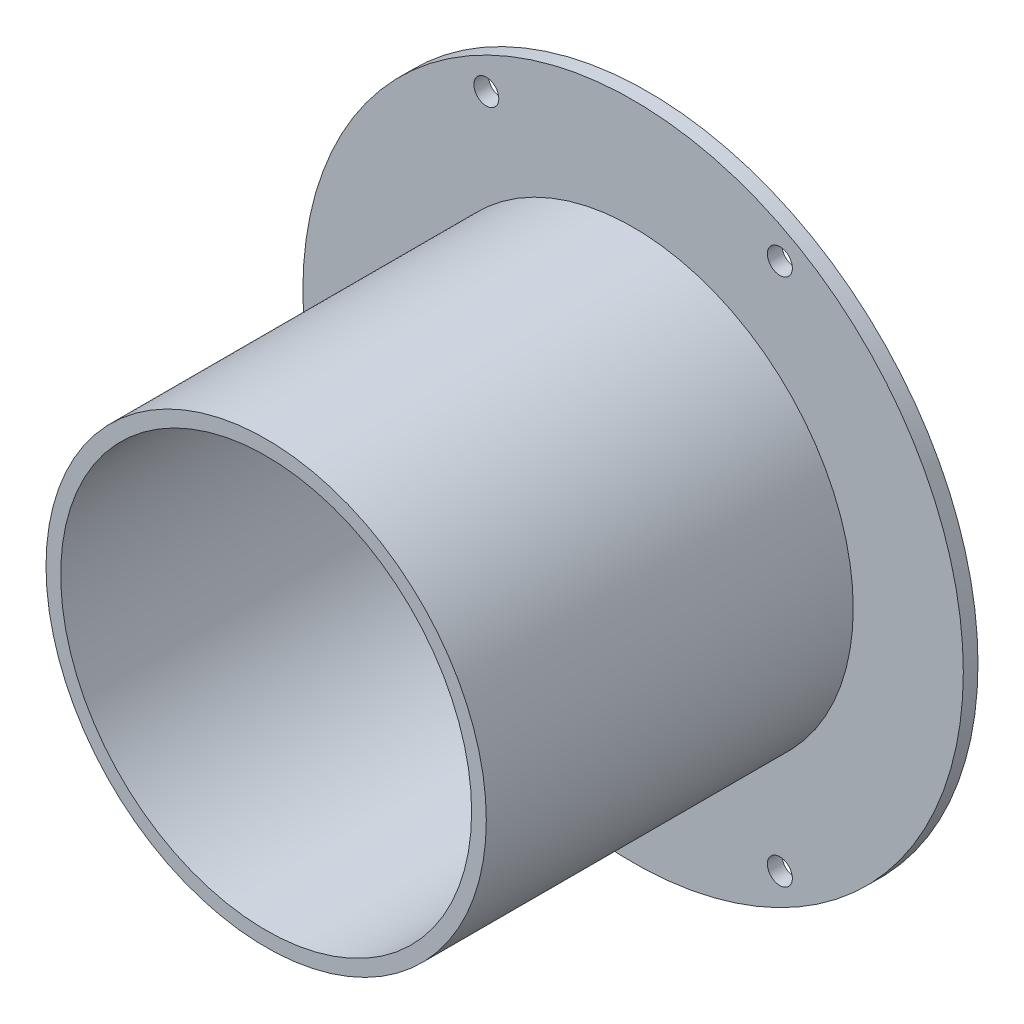
SolidWorks part; units mm, degrees
material "AISI 4340 Steel, normalized"
ref_plane "Front Plane" through (0, 0, 0) normal (0, 0, 1) x (1, 0, 0)
ref_plane "Top Plane" through (0, 0, 0) normal (0, 1, 0) x (1, 0, 0)
ref_plane "Right Plane" through (0, 0, 0) normal (1, 0, 0) x (0, 0, -1)
sketch "Sketch1" plane through (0, 0, 0) normal (0, 0, 1) x (1, 0, 0)
  circle A0 centre (0, 0) radius 45
  circle A1 centre (0, 0) radius 7
extrude "Guard_Flange" add sketch "Sketch1" along normal blind 2
sketch "Sketch2" plane through (0, 0, 0) normal (0, 0, 1) x (1, 0, 0)
  circle A0 centre (0, 0) radius 30
  circle A1 centre (0, 0) radius 28
extrude "Coupling_Contact_Cover" add sketch "Sketch2" along normal blind 50 from offset 2
sketch "Sketch3" plane through (0, 0, 0) normal (0, 0, -1) x (-1, 0, 0)
  circle A0 centre (20, -36) radius 1.7
  circle A1 centre (20, 36) radius 1.7
  circle A2 centre (-20, -36) radius 1.7
  circle A3 centre (-20, 36) radius 1.7
extrude "Four_M3_Guard_Fixing_Holes" cut sketch "Sketch3" against normal blind 2.01
